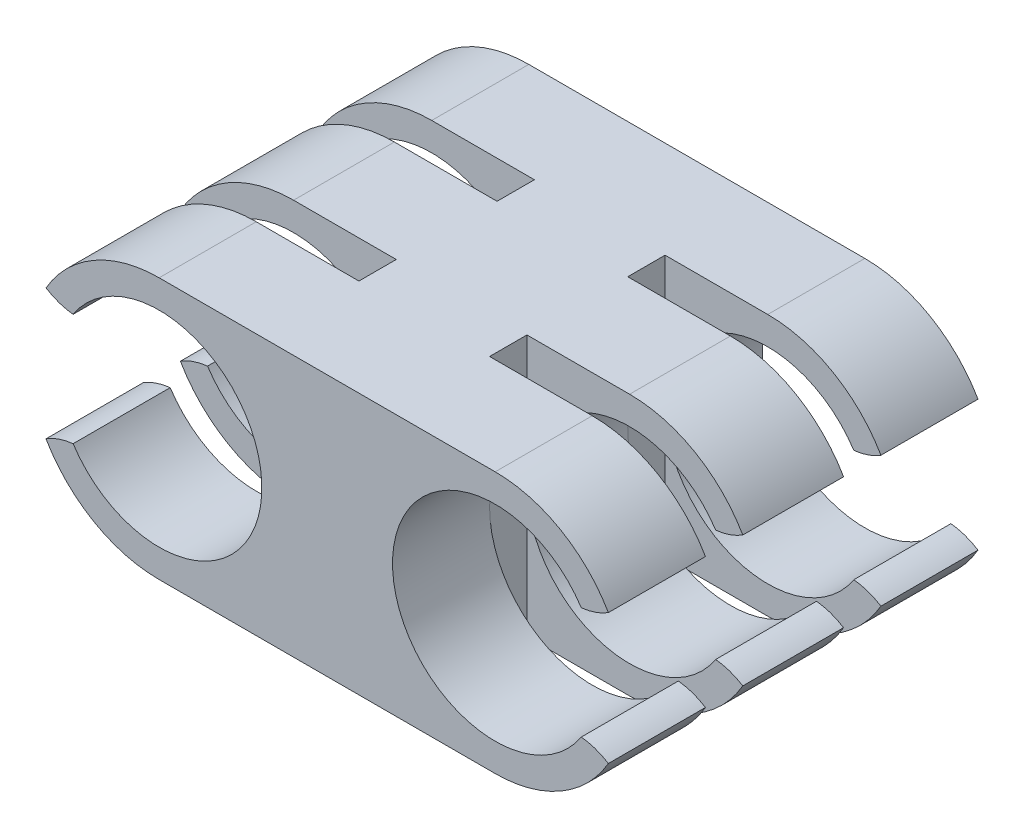
SolidWorks part; units mm, degrees
ref_plane "Front Plane" through (0, 0, 0) normal (0, 0, 1) x (1, 0, 0)
ref_plane "Top Plane" through (0, 0, 0) normal (0, 1, 0) x (1, 0, 0)
ref_plane "Right Plane" through (0, 0, 0) normal (1, 0, 0) x (0, 0, -1)
sketch "Sketch1" plane through (0, 0, 0) normal (0, 0, 1) x (1, 0, 0)
  line L0 (3.0523, 5.8935) -> (12.0523, 5.8935)
  line L5 (14.8023, 2.3935) -> (16.148, 2.3935) construction
  line L12 (3.0523, -1.1065) -> (12.0523, -1.1065)
  line L13 (14.3572, 3.8935) -> (15.2146, 3.8935) construction
  line L14 (15.0834, 0.6435) -> (14.1736, 0.6435) construction
  line L16 (15.0834, 4.1435) -> (14.1736, 4.1435) construction
  line L18 (14.3572, 0.8935) -> (15.2146, 0.8935) construction
  line L19 (7.5523, 5.8935) -> (7.5523, -1.1065) construction
  arc A1 (12.0523, 5.8935) -> (15.0834, 4.1435) centre (12.0523, 2.3935) cw
  arc A2 (14.3572, 3.8935) -> (14.3572, 0.8935) centre (12.0523, 2.3935) ccw
  arc A7 (15.0834, 0.6435) -> (12.0523, -1.1065) centre (12.0523, 2.3935) cw
  arc A8 (0.0212, 0.6435) -> (3.0523, -1.1065) centre (3.0523, 2.3935) ccw
  arc A9 (3.0523, 5.8935) -> (0.0212, 4.1435) centre (3.0523, 2.3935) ccw
  arc A10 (0.7474, 3.8935) -> (0.7474, 0.8935) centre (3.0523, 2.3935) cw
  spline S0 degree 2 poles (14.3572, 3.8935) (14.7541, 3.9358) (15.0834, 4.1435) knots 0 0 0 1 1 1
  spline S1 degree 2 poles (14.3572, 0.8935) (14.7541, 0.8512) (15.0834, 0.6435) knots 0 0 0 1 1 1
  spline S2 degree 2 poles (0.7474, 0.8935) (0.3505, 0.8512) (0.0212, 0.6435) knots 0 0 0 1 1 1
  spline S3 degree 2 poles (0.7474, 3.8935) (0.3505, 3.9358) (0.0212, 4.1435) knots 0 0 0 1 1 1
  point P12 (14.8217, 2.3935)
  point P13 (12.0523, 2.3935)
  point P24 (9.3023, 2.3935)
  point P34 (5.8023, 2.3935)
  dimension "D5" = 3.5
  dimension "D7" = 0.25
  dimension "D2" = 5.5
  dimension "D3" = 7
  dimension "D1" = 9
  dimension "D4" = 7
extrude "Boss-Extrude1" add sketch "Sketch1" along normal blind 9.9
sketch "Sketch4" plane through (0, 5.8935, 0) normal (0, 1, 0) x (1, 0, 0)
  line L0 (0.0212, -2.6) -> (0.0212, -3.6)
  line L1 (0.0212, -9.9) -> (0.0212, 0) construction
  line L2 (15.0834, -9.9) -> (15.0834, 0) construction
  line L3 (0.0212, -3.1) -> (5.8023, -3.1) construction
  line L4 (0.0212, -6.8) -> (15.0834, -6.8) construction
  line L6 (12.0523, 0) -> (3.0523, 0) construction
  line L7 (12.0523, -9.9) -> (3.0523, -9.9) construction
  line L8 (0.0212, -2.6) -> (5.8023, -2.6)
  line L10 (0.0212, -3.6) -> (5.8023, -3.6)
  line L13 (7.5523, -3.1) -> (7.5523, -6.8) construction
  line L19 (15.0834, -2.6) -> (15.0834, -3.6)
  line L20 (9.3023, -2.6) -> (15.0834, -2.6)
  line L22 (5.8023, -2.6) -> (5.8023, -3.6)
  line L24 (9.3023, -2.6) -> (9.3023, -3.6)
  line L25 (0.0212, -4.95) -> (15.0834, -4.95) construction
  line L26 (9.3023, -7.3) -> (15.0834, -7.3)
  line L27 (15.0834, -7.3) -> (15.0834, -6.3)
  line L28 (9.3023, -3.1) -> (15.0834, -3.1) construction
  line L29 (9.3023, -6.3) -> (15.0834, -6.3)
  line L30 (9.3023, -7.3) -> (9.3023, -6.3)
  line L31 (9.3023, -3.6) -> (15.0834, -3.6)
  line L32 (0.0212, -7.3) -> (5.8023, -7.3)
  line L33 (0.0212, -7.3) -> (0.0212, -6.3)
  line L34 (0.0212, -6.3) -> (5.8023, -6.3)
  line L35 (5.8023, -7.3) -> (5.8023, -6.3)
  point P0 (7.5523, -3.1)
  point P17 (7.5523, -6.8)
  point P25 (0.0212, -3.1)
  point P28 (0.0212, -6.8)
  dimension "D1" = 3.1
  dimension "D2" = 3.1
  dimension "D5" = 1
extrude "Cut-Extrude3" cut sketch "Sketch4" against normal through all
